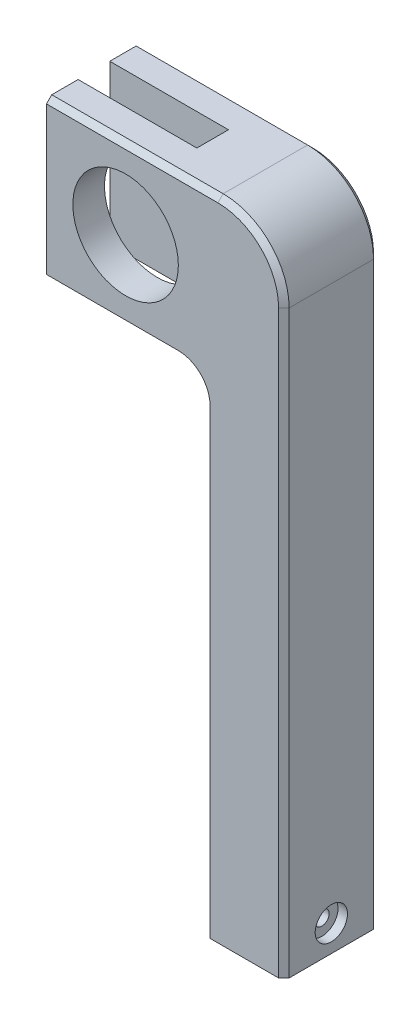
SolidWorks part; units mm, degrees
ref_plane "Front Plane" through (0, 0, 0) normal (0, 0, 1) x (1, 0, 0)
ref_plane "Top Plane" through (0, 0, 0) normal (0, 1, 0) x (1, 0, 0)
ref_plane "Right Plane" through (0, 0, 0) normal (1, 0, 0) x (0, 0, -1)
sketch "Sketch1" plane through (0, 0, 0) normal (0, 0, 1) x (1, 0, 0)
  line L0 (0, 0) -> (-30, 0)
  line L9 (-30, 185) -> (-30, 0)
  line L10 (-30, 185) -> (-90, 185)
  line L11 (-90, 185) -> (-90, 245)
  line L12 (-90, 245) -> (0, 245)
  line L13 (0, 245) -> (0, 0)
  dimension "D1" = 245
  dimension "D2" = 90
  dimension "D3" = 30
  dimension "D4" = 60
extrude "Boss-Extrude1" add sketch "Sketch1" against normal mid plane 36
sketch "Sketch3" plane through (0, 245, 0) normal (0, 1, 0) x (1, 0, 0)
  line L0 (-90, 18) -> (-90, -18) construction
  line L1 (-45, -6) -> (-90, -6)
  line L2 (-45, -6) -> (-45, 6)
  line L3 (-45, 6) -> (-90, 6)
  line L4 (-90, -6) -> (-90, 6)
  line L5 (-45, -6) -> (-90, 6) construction
  line L6 (-45, 6) -> (-90, -6) construction
  line L7 (-90, 0) -> (0, 0) construction
  point P0 (-67.5, 0)
  dimension "D1" = 12
  dimension "D2" = 45
extrude "Cut-Extrude1" cut sketch "Sketch3" against normal up to next
fillet "Fillet1" radius 25 1 edges at (0, 245, 0)
fillet "Fillet2" radius 10 1 edges at (-30, 185, 0)
sketch "Sketch4" plane through (0, 0, 18) normal (0, 0, 1) x (1, 0, 0)
  line L0 (-90, 245) -> (-90, 185) construction
  line L1 (-90, 215) -> (-39.4804, 215) construction
  circle A0 centre (-60, 215) radius 20
  dimension "D2" = 40
  dimension "D1" = 30
extrude "Cut-Extrude2" cut sketch "Sketch4" against normal up to surface (12 mm away) up to face at (-67.5, 215, 6)
sketch "Sketch5" plane through (0, 0, -18) normal (0, 0, -1) x (-1, 0, 0)
  line L0 (90, 215) -> (42.6224, 215) construction
  line L1 (90, 245) -> (90, 185) construction
  circle A0 centre (60, 215) radius 13
  dimension "D1" = 30
  dimension "D2" = 26
extrude "Cut-Extrude3" cut sketch "Sketch5" against normal up to next
chamfer "Chamfer1" distance 2 angle 45 12 edges at (-65, 185, 18) (-32.9289, 182.0711, 18) (-30, 87.5, 18) (-65, 185, -18) (-32.9289, 182.0711, -18) (-30, 87.5, -18) (-57.5, 245, -18) (-7.3223, 237.6777, -18) (0, 110, -18) (-57.5, 245, 18) (-7.3223, 237.6777, 18) (0, 110, 18)
sketch "Sketch9" plane through (0, 0, 0) normal (1, 0, 0) x (0, 0, -1)
  line L0 (0, 0) -> (0, 10) construction
  line L1 (16, 0) -> (-16, 0) construction
  point P1 (0, 10)
  dimension "D1" = 10
hole_wizard "CBORE for M5 Hex Head Bolt1" positions "Sketch9" profile "Sketch10" counterbore size "M5" standard "ANSI Metric" end condition up to next
sketch "Sketch10" plane through (0, 10, 0) normal (0, 1, 0) x (0, 0, -1)
  line L0 (0, 0) -> (0, 30)
  line L1 (0, 30) -> (2.75, 30)
  line L3 (2.75, 30) -> (2.75, 3.58)
  line L4 (2.75, 3.58) -> (6.12, 3.58)
  line L5 (6.12, 3.58) -> (6.12, 0)
  line L7 (6.12, 0) -> (0, 0)
  line L11 (0, -6.35) -> (0, 107.95) construction
  dimension "Thru Hole Dia." = 5.5
  dimension "Thru Hole Depth" = 30
  dimension "C'Bore Dia." = 12.24
  dimension "C'Bore Depth" = 3.58
sketch "Sketch11" plane through (-90, 0, 0) normal (-1, 0, 0) x (0, 0, 1)
  line L0 (-16, 185) -> (-6, 185) construction
  line L1 (-12, 190) -> (12, 190) construction
  line L2 (-12, 190) -> (-12, 240) construction
  line L3 (-12, 240) -> (12, 240) construction
  line L4 (12, 190) -> (12, 240) construction
  line L5 (-12, 190) -> (12, 240) construction
  line L6 (-12, 240) -> (12, 190) construction
  line L7 (18, 243) -> (18, 187) construction
  line L8 (-18, 243) -> (-18, 187) construction
  point P1 (12, 240)
  point P2 (-12, 190)
  point P3 (-12, 240)
  point P4 (12, 190)
  dimension "D1" = 50
  dimension "D2" = 5
  dimension "D3" = 6
  dimension "D4" = 6
hole_wizard "Ø3.0mm Dowel Hole1" positions "Sketch11" profile "Sketch12" hole size "Ø3.0" standard "ANSI Metric"
sketch "Sketch12" plane through (-90, 240, 12) normal (0, 1, 0) x (0, 0, 1)
  line L0 (0, 0) -> (0, 20.9013)
  line L1 (0, 20.9013) -> (1.5, 20)
  line L2 (1.5, 20) -> (1.5, 0)
  line L5 (1.5, 0) -> (0, 0)
  line L10 (0, 20.9013) -> (-1.5, 20) construction
  line L11 (0, -6.35) -> (0, 107.95) construction
  dimension "Hole Dia." = 3
  dimension "Hole Depth" = 20
  dimension "Drill Angle" = 118
